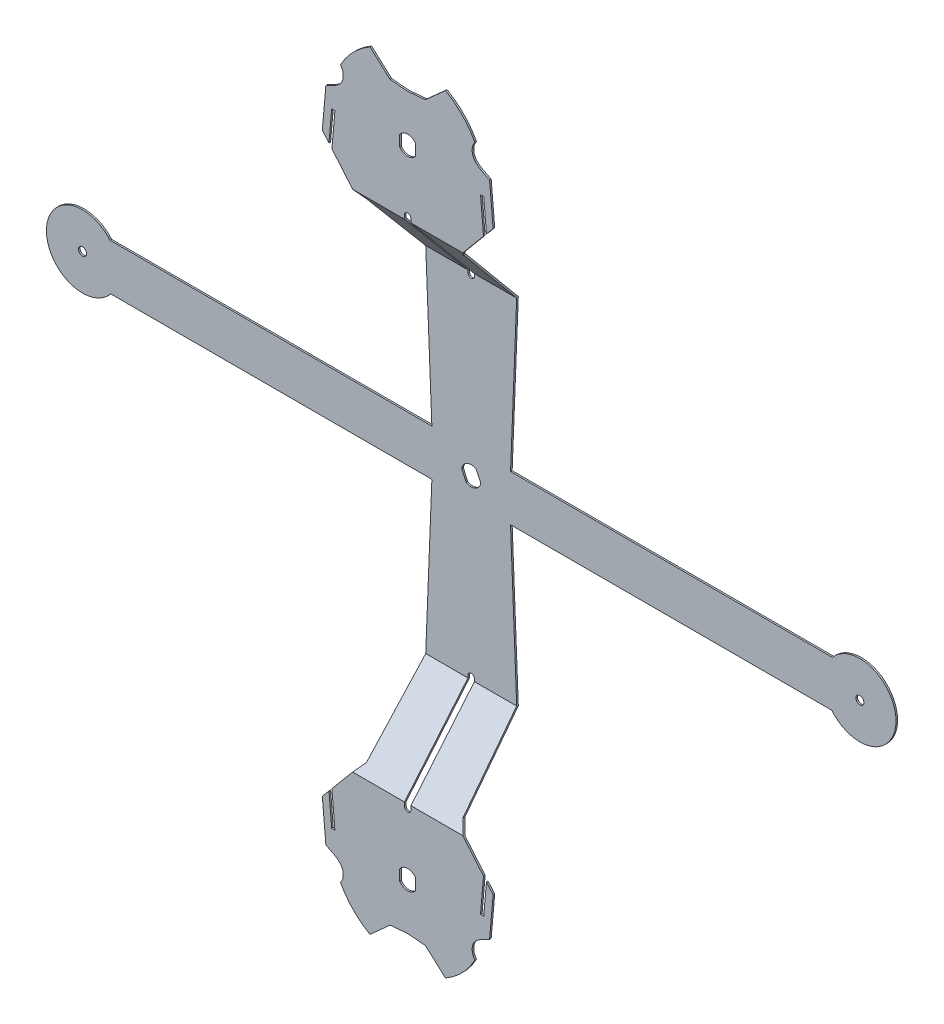
SolidWorks part; units mm, degrees
ref_plane "Alzado" through (0, 0, 0) normal (0, 0, 1) x (1, 0, 0)
ref_plane "Planta" through (0, 0, 0) normal (0, 1, 0) x (1, 0, 0)
ref_plane "Vista lateral" through (0, 0, 0) normal (1, 0, 0) x (0, 0, -1)
sketch "Croquis1" plane through (0, 0, 0) normal (1, 0, 0) x (0, 0, -1)
  line L0 (-18.5, -110) -> (-18.5, 110)
  line L1 (-18.5, 110) -> (-58.0314, 157.1117)
  line L2 (0, 0) -> (-82.8072, 0) construction
  line L3 (-58.0314, 157.1117) -> (-58.0314, 248)
  line L4 (-18.5, -110) -> (-58.0314, -157.1117)
  line L5 (-58.0314, -157.1117) -> (-58.0314, -248)
  line L6 (-57.0314, -157.4757) -> (-57.0314, -248)
  line L7 (-17.5, -110.364) -> (-57.0314, -157.4757)
  line L8 (-17.5, -110.364) -> (-17.5, 110.364)
  line L9 (-17.5, 110.364) -> (-57.0314, 157.4757)
  line L10 (-57.0314, 157.4757) -> (-57.0314, 248)
  line L11 (-58.0314, 248) -> (-57.0314, 248)
  line L12 (-58.0314, -248) -> (-57.0314, -248)
  point P9 (-18.5, 0)
  dimension "D1" = 18.5
  dimension "D2" = 50
  dimension "D3" = 61.5
  dimension "D4" = 110
  dimension "D5" = 496
  dimension "D6" = 1
extrude "Saliente-Extruir1" add sketch "Croquis1" along normal mid plane 542
sketch "Croquis5" plane through (0, 0, 0) normal (0, 0, 1) x (1, 0, 0)
  line L0 (-923.9507, 561.734) -> (-241.388, 573.6482) construction
sketch "Croquis2" plane through (0, 0, 0) normal (0, 0, 1) x (1, 0, 0)
  line L1 (0, 277.0309) -> (0, -277.0309) construction
  line L7 (-30, 152) -> (-24.5, 14.5602)
  line L9 (-300.4496, 0) -> (300.4496, 0) construction
  line L10 (0, 108.5) -> (0, 159.5) construction
  line L11 (-2, 108.5) -> (-2, 159.5)
  line L12 (2, 108.5) -> (2, 159.5)
  line L13 (-30, 152) -> (-47.205, 172.5041)
  line L14 (-53.1684, 179.6111) -> (-50.9701, 204.7381)
  line L15 (-23.5, 239.2795) -> (-11, 228.0419)
  line L31 (-224.8463, 14.5602) -> (-24.5, 14.5602)
  line L33 (0, 28.2902) -> (-24.5, 14.1451) construction
  line L34 (-11, 228.0419) -> (0, 227.0795)
  line L35 (-49.0231, 174.6708) -> (-47.3316, 194.0041)
  line L36 (-47.3316, 194.0041) -> (-45.324, 194.0041)
  line L37 (-45.324, 194.0041) -> (-47.205, 172.5041)
  line L38 (-49.0231, 174.6708) -> (-53.1684, 179.6111)
  line L39 (-24.5, 14.1451) -> (-24.5, -14.1451) construction
  line L40 (-24.5, -14.1451) -> (0, -28.2902) construction
  line L41 (0, -28.2902) -> (24.5, -14.1451) construction
  line L42 (24.5, -14.1451) -> (24.5, 14.1451) construction
  line L43 (24.5, 14.1451) -> (0, 28.2902) construction
  line L44 (-224.5024, -14.1451) -> (-24.5, -14.1451)
  line L45 (0, -108.5) -> (0, -159.5) construction
  line L46 (-2, -108.5) -> (-2, -159.5)
  line L47 (2, -108.5) -> (2, -159.5)
  line L48 (-30, -152) -> (-24.5, -14.5602)
  line L49 (-30, -152) -> (-47.205, -172.5041)
  line L50 (-45.324, -194.0041) -> (-47.205, -172.5041)
  line L51 (-47.3316, -194.0041) -> (-45.324, -194.0041)
  line L52 (-49.0231, -174.6708) -> (-47.3316, -194.0041)
  line L53 (-49.0231, -174.6708) -> (-53.1684, -179.6111)
  line L54 (-53.1684, -179.6111) -> (-50.9701, -204.7381)
  line L55 (-23.5, -239.2795) -> (-11, -228.0419)
  line L56 (-11, -228.0419) -> (0, -227.0795)
  line L57 (11, -228.0419) -> (0, -227.0795)
  line L58 (23.5, -239.2795) -> (11, -228.0419)
  line L59 (53.1684, -179.6111) -> (50.9701, -204.7381)
  line L60 (49.0231, -174.6708) -> (53.1684, -179.6111)
  line L61 (49.0231, -174.6708) -> (47.3316, -194.0041)
  line L62 (47.3316, -194.0041) -> (45.324, -194.0041)
  line L63 (45.324, -194.0041) -> (47.205, -172.5041)
  line L64 (30, -152) -> (47.205, -172.5041)
  line L65 (30, -152) -> (24.5, -14.5602)
  line L66 (224.5024, -14.1451) -> (24.5, -14.1451)
  line L67 (49.0231, 174.6708) -> (53.1684, 179.6111)
  line L68 (45.324, 194.0041) -> (47.205, 172.5041)
  line L69 (47.3316, 194.0041) -> (45.324, 194.0041)
  line L70 (49.0231, 174.6708) -> (47.3316, 194.0041)
  line L71 (11, 228.0419) -> (0, 227.0795)
  line L72 (224.8463, 14.5602) -> (24.5, 14.5602)
  line L73 (23.5, 239.2795) -> (11, 228.0419)
  line L74 (53.1684, 179.6111) -> (50.9701, 204.7381)
  line L75 (30, 152) -> (47.205, 172.5041)
  line L76 (30, 152) -> (24.5, 14.5602)
  line L77 (-24.5, -14.5602) -> (-24.5, -14.1451)
  line L78 (24.5, -14.5602) -> (24.5, -14.1451)
  line L80 (-300.4496, 277.0309) -> (300.4496, 277.0309)
  line L81 (-300.4496, 277.0309) -> (-300.4496, -277.0309)
  line L82 (-300.4496, -277.0309) -> (300.4496, -277.0309)
  line L83 (300.4496, 277.0309) -> (300.4496, -277.0309)
  line L84 (-300.4496, 277.0309) -> (300.4496, -277.0309) construction
  line L85 (-300.4496, -277.0309) -> (300.4496, 277.0309) construction
  circle A9 centre (0, 0) radius 247.5 construction
  arc A10 (-224.8463, 14.5602) -> (-224.5024, -14.1451) centre (-242, 0) ccw
  circle A11 centre (0, 0) radius 28.5 construction
  arc A12 (-2, 108.5) -> (2, 108.5) centre (0, 108.5) ccw
  arc A13 (2, 159.5) -> (-2, 159.5) centre (0, 159.5) ccw
  arc A14 (-41.8968, 220.3811) -> (-23.5, 239.2795) centre (0, 198) cw
  circle A15 centre (0, 198) radius 47.5 construction
  circle A16 centre (0, 0) radius 24.5 construction
  arc A17 (-2, -108.5) -> (2, -108.5) centre (0, -108.5) cw
  arc A18 (2, -159.5) -> (-2, -159.5) centre (0, -159.5) cw
  arc A19 (-41.8968, -220.3811) -> (-23.5, -239.2795) centre (0, -198) ccw
  arc A20 (41.8968, -220.3811) -> (23.5, -239.2795) centre (0, -198) cw
  arc A21 (41.8968, 220.3811) -> (23.5, 239.2795) centre (0, 198) ccw
  arc A22 (224.8463, 14.5602) -> (224.5024, -14.1451) centre (242, 0) cw
  spline S0 degree 3 poles (-50.9701, 204.7381) (-47.793, 206.2687) (-40.7871, 209.0246) (-39.8831, 216.4184) (-40.7368, 219.1761) (-41.8968, 220.3811) knots 0 0 0 0 0.610721 0.773573 1 1 1 1
  spline S1 degree 3 poles (-50.9701, -204.7381) (-47.793, -206.2687) (-40.7871, -209.0246) (-39.8831, -216.4184) (-40.7368, -219.1761) (-41.8968, -220.3811) knots 0 0 0 0 0.610721 0.773573 1 1 1 1
  spline S2 degree 3 poles (50.9701, -204.7381) (47.793, -206.2687) (40.7871, -209.0246) (39.8831, -216.4184) (40.7368, -219.1761) (41.8968, -220.3811) knots 0 0 0 0 0.610721 0.773573 1 1 1 1
  spline S3 degree 3 poles (50.9701, 204.7381) (47.793, 206.2687) (40.7871, 209.0246) (39.8831, 216.4184) (40.7368, 219.1761) (41.8968, 220.3811) knots 0 0 0 0 0.610721 0.773573 1 1 1 1
  point P6 (0, 0)
  point P7 (0, 0)
  point P15 (0, 134)
  point P48 (0, -134)
  dimension "D1" = 495
  dimension "D3" = 45
  dimension "D9" = 198
  dimension "D4" = 57
  dimension "D6" = 49
  dimension "D10" = 134
  dimension "D14" = 152
  dimension "D5" = 95
  dimension "D23" = 21.6
  dimension "D2" = 242
  dimension "D7" = 51
  dimension "D8" = 4
  dimension "D11" = 30
  dimension "D12" = 2
  dimension "D13" = 50
  dimension "D15" = 25.1271
  dimension "D16" = 5
  dimension "D17" = 179.6111
  dimension "D18" = 5
  dimension "D19" = 11
  dimension "D20" = 23.5
  dimension "D21" = 12.2
  dimension "D22" = 21.5
sketch "Croquis4" plane through (0, 0, 0) normal (0, 0, 1) x (1, 0, 0)
  line L0 (-326.6263, 0) -> (326.6263, 0) construction
  line L1 (0, 278.5393) -> (0, -278.5393) construction
  line L2 (-5, -194.6834) -> (5, -201.3166) construction
  line L3 (-5, 201.3166) -> (5, 201.3166) construction
  line L4 (-5, 201.3166) -> (-5, 194.6834)
  line L5 (-5, 194.6834) -> (5, 194.6834) construction
  line L6 (5, 201.3166) -> (5, 194.6834)
  line L7 (-5, 201.3166) -> (5, 194.6834) construction
  line L8 (-5, 194.6834) -> (5, 201.3166) construction
  line L9 (-5, -201.3166) -> (5, -194.6834) construction
  line L10 (-5, -194.6834) -> (5, -194.6834) construction
  line L11 (-5, -201.3166) -> (5, -201.3166) construction
  line L12 (5, -201.3166) -> (5, -194.6834)
  line L13 (-5, -201.3166) -> (-5, -194.6834)
  line L26 (-5.9332, 0.8928) -> (3.1299, 5.119) construction
  line L27 (-5.9332, 0.8928) -> (-3.1299, -5.119)
  line L28 (3.1299, 5.119) -> (5.9332, -0.8928)
  line L29 (-3.1299, -5.119) -> (5.9332, -0.8928) construction
  line L30 (0, 0) -> (-1.4017, 3.0059) construction
  arc A0 (-5, 194.6834) -> (5, 194.6834) centre (0, 198) ccw
  arc A1 (-3.1299, -5.119) -> (5.9332, -0.8928) centre (0, 0) ccw
  arc A4 (5, 201.3166) -> (-5, 201.3166) centre (0, 198) ccw
  arc A5 (5, -201.3166) -> (-5, -201.3166) centre (0, -198) cw
  arc A6 (-5, -194.6834) -> (5, -194.6834) centre (0, -198) cw
  circle A7 centre (-242, 0) radius 2.5
  arc A10 (3.1299, 5.119) -> (-5.9332, 0.8928) centre (0, 0) ccw
  circle A11 centre (242, 0) radius 2.5
  point P4 (0, 0)
  point P8 (0, 0)
  dimension "D4" = 10
  dimension "D5" = 12
  dimension "D6" = 12
  dimension "D2" = 5
  dimension "D1" = 198
  dimension "D8" = 10
  dimension "D9" = 25
extrude "Cortar-Extruir9" cut sketch "Croquis4" against normal through all both and the other way through all
extrude "Cortar-Extruir11" cut sketch "Croquis2" against normal through all both and the other way through all contours L83 L80 L81 L82 S3 L74 L67 L70 L69 L68 L75 L76 L72 A22 L66 L78 L65 L64 L63 L62 L61 L60 L59 S2 A20 L58 L57 L56 L55 A19 S1 L54 L53 L52 L51 L50 L49 L48 L77 L44 A10 L31 L7 L13 L37 L36 L35 L38 L14 S0 | L47 A18 L46 A17 | L12 A13 L11 A12
